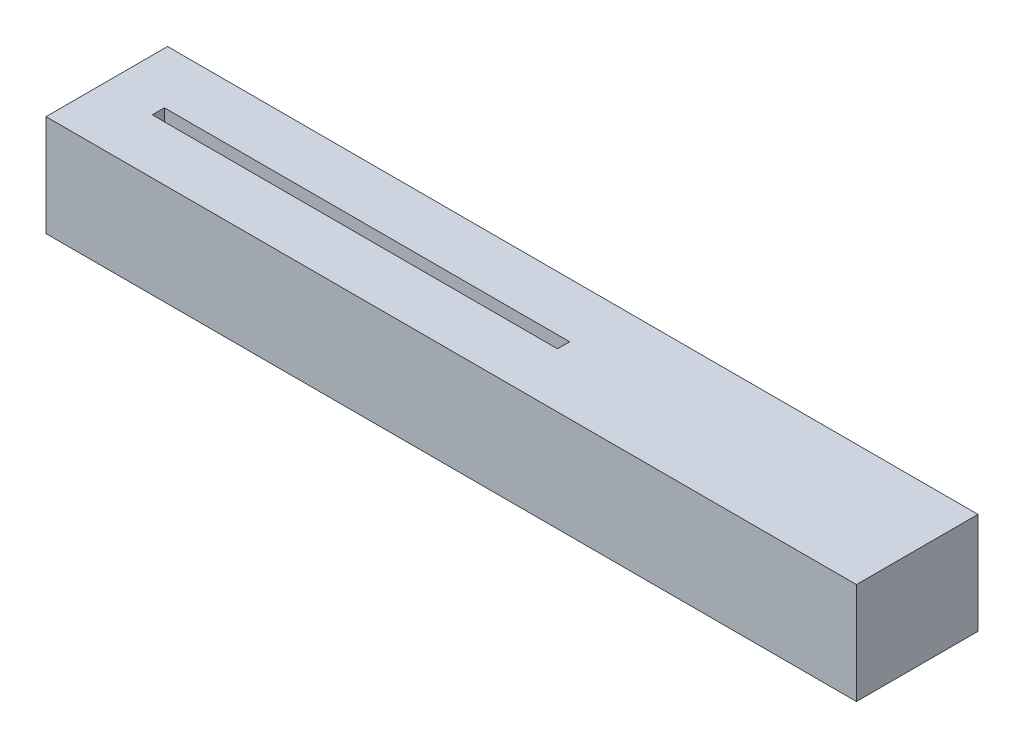
SolidWorks part; units mm, degrees
ref_plane "前视基准面" through (0, 0, 0) normal (0, 0, 1) x (1, 0, 0)
ref_plane "上视基准面" through (0, 0, 0) normal (0, 1, 0) x (1, 0, 0)
ref_plane "右视基准面" through (0, 0, 0) normal (1, 0, 0) x (0, 0, -1)
other "Configuration Table"
sketch "草图1" plane through (0, 0, 0) normal (0, 1, 0) x (1, 0, 0)
  line L0 (0, 3) -> (40, 3) construction
  line L1 (0, 0) -> (40, 0)
  line L2 (0, 0) -> (0, 6)
  line L3 (0, 6) -> (40, 6)
  line L4 (40, 0) -> (40, 6)
  line L5 (2.5443, 2.7) -> (22.5443, 2.7)
  line L6 (2.5443, 3) -> (22.5443, 3)
  line L7 (2.5443, 2.7) -> (2.5443, 3.3)
  line L8 (2.5443, 3.3) -> (22.5443, 3.3)
  line L9 (22.5443, 2.7) -> (22.5443, 3.3)
  dimension "D1" = 40
  dimension "D2" = 6
  dimension "D3" = 0.3
  dimension "D4" = 20
extrude "凸台-拉伸1" add sketch "草图1" along normal blind 5 contours L2 L0 L7 L8 L9 L4 L3 | L0 L2 L1 L4 L9 L5 L7
